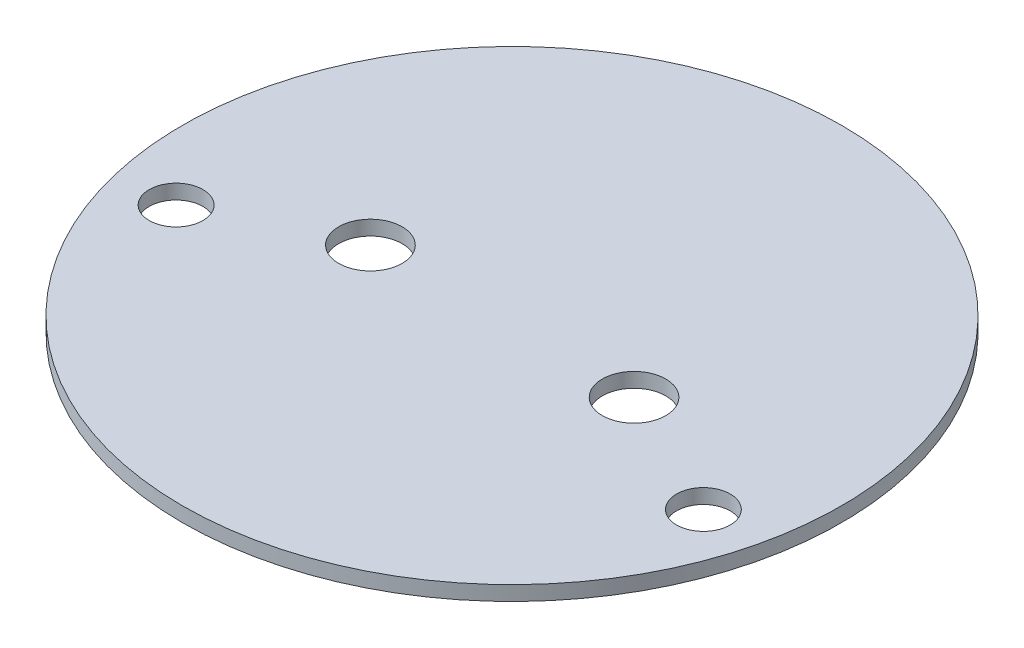
SolidWorks part; units mm, degrees
material "ABS"
ref_plane "Front Plane" through (0, 0, 0) normal (0, 0, 1) x (1, 0, 0)
ref_plane "Top Plane" through (0, 0, 0) normal (0, 1, 0) x (1, 0, 0)
ref_plane "Right Plane" through (0, 0, 0) normal (1, 0, 0) x (0, 0, -1)
sketch "Sketch1" plane through (0, 0, 0) normal (0, 1, 0) x (1, 0, 0)
  line L0 (-27, -7.4) -> (27, -7.4) construction
  line L1 (-13.5, -1) -> (13.5, -1) construction
  circle A0 centre (0, 0) radius 33.75
  circle A1 centre (-27, -7.4) radius 2.75
  circle A2 centre (27, -7.4) radius 2.75
  circle A3 centre (-13.5, -1) radius 3.25
  circle A4 centre (13.5, -1) radius 3.25
  point P7 (0, -7.4)
  point P12 (0, -1)
  dimension "D2" = 5.5
  dimension "D3" = 67.5
  dimension "D5" = 6.5
  dimension "D1" = 54
  dimension "D4" = 7.4
  dimension "D6" = 1
  dimension "D7" = 27
extrude "Boss-Extrude1" add sketch "Sketch1" along normal blind 1.5
